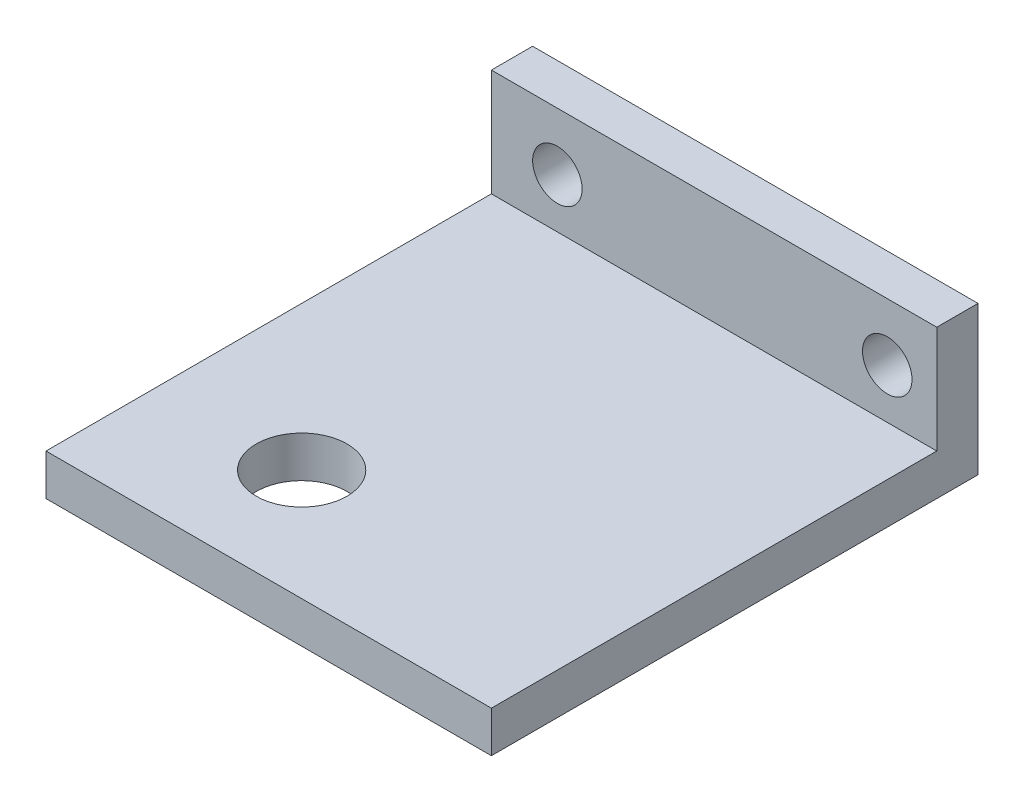
SolidWorks part; units mm, degrees
ref_plane "Plan de face" through (0, 0, 0) normal (0, 0, 1) x (1, 0, 0)
ref_plane "Plan de dessus" through (0, 0, 0) normal (0, 1, 0) x (1, 0, 0)
ref_plane "Plan de droite" through (0, 0, 0) normal (1, 0, 0) x (0, 0, -1)
sketch "Esquisse1" plane through (0, 0, 0) normal (0, 0, 1) x (1, 0, 0)
  line L1 (-27, -9) -> (27, -9)
  line L2 (-27, -9) -> (-27, 9)
  line L3 (-27, 9) -> (27, 9)
  line L4 (27, -9) -> (27, 9)
  line L5 (-27, -9) -> (27, 9) construction
  line L6 (-27, 9) -> (27, -9) construction
  circle A0 centre (-19, 2) radius 3
  circle A1 centre (21, 2) radius 3
  point P0 (0, 0)
  dimension "D3" = 6
  dimension "D1" = 54
  dimension "D2" = 18
  dimension "D4" = 7
  dimension "D5" = 8
  dimension "D6" = 2
extrude "Boss.-Extru.1" add sketch "Esquisse1" along normal blind 59
sketch "Esquisse2" plane through (0, 9, 0) normal (0, 1, 0) x (1, 0, 0)
  line L8 (22, -5) -> (-22, -5)
  line L9 (-22, -5) -> (-22, -54)
  line L10 (-22, -54) -> (22, -54)
  line L11 (22, -54) -> (22, -5)
  line L12 (42.5059, -5) -> (-47.38, -5)
  line L13 (-47.38, -5) -> (-47.38, -79.5648)
  line L14 (-47.38, -79.5648) -> (42.5059, -79.5648)
  line L15 (42.5059, -79.5648) -> (42.5059, -5)
  dimension "D1" = 5
extrude "Enlèv. mat.-Extru.1" cut sketch "Esquisse2" against normal blind 13
hole_wizard "Dégagement M101" positions "Esquisse4" profile "Esquisse3" hole size "M10" standard "JIS" end condition through all
sketch "Esquisse4" plane through (0, -4, 0) normal (0, 1, 0) x (1, 0, 0)
  point P0 (-9.5, -45.5022)
sketch "Esquisse3" plane through (-9.5, -4, 45.5022) normal (1, 0, 0) x (0, 0, 1)
  line L0 (0, 0) -> (0, 5)
  line L1 (0, 5) -> (5.5, 5)
  line L2 (5.5, 5) -> (5.5, 0)
  line L5 (5.5, 0) -> (0, 0)
  line L11 (0, -6.35) -> (0, 107.95) construction
  dimension "Diamètre du perçage jusqu'au prochain" = 11
  dimension "Profondeur du perçage jusqu'au prochain" = 5
